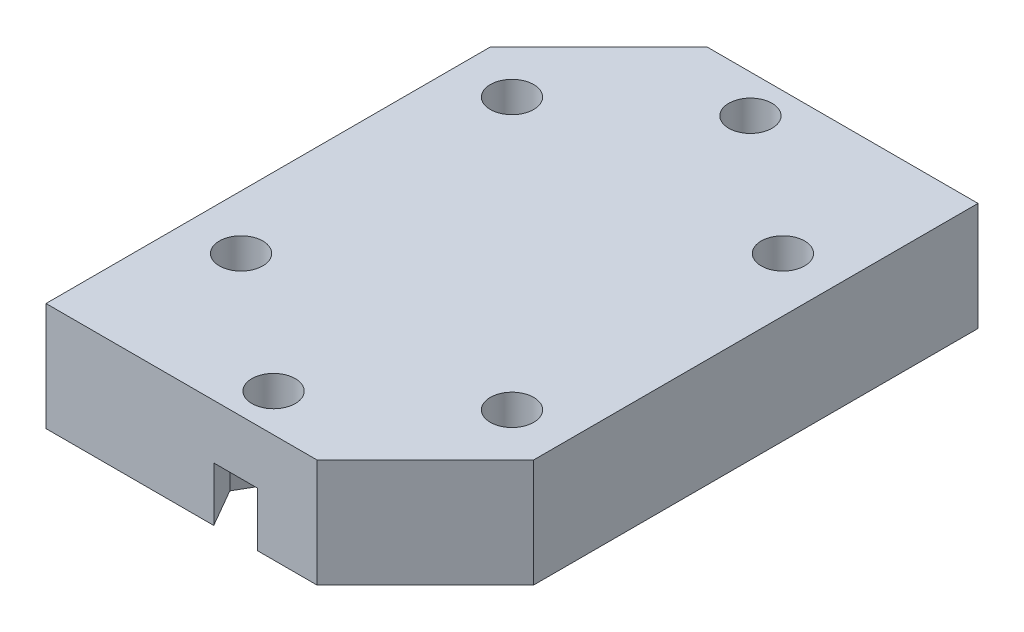
SolidWorks part; units mm, degrees
ref_plane "Front Plane" through (0, 0, 0) normal (0, 0, 1) x (1, 0, 0)
ref_plane "Top Plane" through (0, 0, 0) normal (0, 1, 0) x (1, 0, 0)
ref_plane "Right Plane" through (0, 0, 0) normal (1, 0, 0) x (0, 0, -1)
sketch "Sketch1" plane through (0, 0, 0) normal (0, 1, 0) x (1, 0, 0)
  line L11 (-12.5, 12.5) -> (12.5, -12.5) construction
  line L12 (-12.5, -12.5) -> (12.5, 12.5) construction
  line L14 (0, 25.5) -> (0, -25.5) construction
  line L15 (-17.5, 25.5) -> (17.5, 25.5)
  line L16 (-17.5, 25.5) -> (-17.5, -25.5)
  line L17 (-17.5, -25.5) -> (17.5, -25.5)
  line L18 (17.5, 25.5) -> (17.5, -25.5)
  line L19 (-17.5, 25.5) -> (17.5, -25.5) construction
  line L20 (-17.5, -25.5) -> (17.5, 25.5) construction
  circle A0 centre (-12.5, 12.5) radius 2
  circle A1 centre (12.5, 12.5) radius 2
  circle A2 centre (12.5, -12.5) radius 2
  circle A3 centre (-12.5, -12.5) radius 2
  circle A4 centre (0, 22) radius 2
  circle A5 centre (0, -22) radius 2
  point P0 (0, 0)
  point P6 (0, 0)
  point P19 (0, 0)
  dimension "D4" = 4
  dimension "D7" = 4
  dimension "D8" = 44
  dimension "D1" = 25
  dimension "D3" = 25
  dimension "D5" = 51
  dimension "D6" = 35
extrude "Boss-Extrude1" add sketch "Sketch1" along normal blind 10
sketch "Sketch2" plane through (0, 0, 0) normal (0, 1, 0) x (1, 0, 0)
  line L0 (17.5, 0) -> (-17.5, 0) construction
  line L1 (4.0415, 22) -> (2.0207, 25.5)
  line L2 (2.0207, 25.5) -> (-2.0207, 25.5)
  line L3 (-2.0207, 25.5) -> (-4.0415, 22)
  line L4 (-4.0415, 22) -> (-2.0207, 18.5)
  line L5 (-2.0207, 18.5) -> (2.0207, 18.5)
  line L6 (2.0207, 18.5) -> (4.0415, 22)
  line L7 (17.5, -25.5) -> (17.5, 25.5) construction
  line L8 (-17.5, 25.5) -> (-17.5, -25.5) construction
  line L10 (4.0415, -22) -> (2.0207, -18.5)
  line L11 (2.0207, -18.5) -> (-2.0207, -18.5)
  line L12 (-2.0207, -18.5) -> (-4.0415, -22)
  line L13 (-4.0415, -22) -> (-2.0207, -25.5)
  line L14 (-2.0207, -25.5) -> (2.0207, -25.5)
  line L15 (2.0207, -25.5) -> (4.0415, -22)
  circle A0 centre (0, 22) radius 3.5 construction
  circle A1 centre (0, -22) radius 3.5 construction
  dimension "D2" = 7
  dimension "D1" = 7
extrude "Cut-Extrude4" cut sketch "Sketch2" along normal blind 5
sketch "Sketch4" plane through (0, 0, 0) normal (0, 1, 0) x (1, 0, 0)
  line L0 (-7.5, 25.5) -> (-17.5, 15.5)
  line L1 (17.5, 25.5) -> (-17.5, 25.5) construction
  line L2 (-17.5, 25.5) -> (-17.5, -25.5) construction
  line L3 (17.5, -15.5) -> (7.5, -25.5)
  line L4 (17.5, -25.5) -> (17.5, 25.5) construction
  line L5 (-17.5, -25.5) -> (17.5, -25.5) construction
  line L6 (-17.5, 15.5) -> (-17.5, 25.5)
  line L7 (-17.5, 25.5) -> (-7.5, 25.5)
  line L8 (17.5, -15.5) -> (17.5, -25.5)
  line L9 (17.5, -25.5) -> (7.5, -25.5)
  dimension "D1" = 10
  dimension "D2" = 10
  dimension "D3" = 10
  dimension "D4" = 10
extrude "Cut-Extrude5" cut sketch "Sketch4" along normal through all contours L3 L9 L8 | L0 L6 L7
